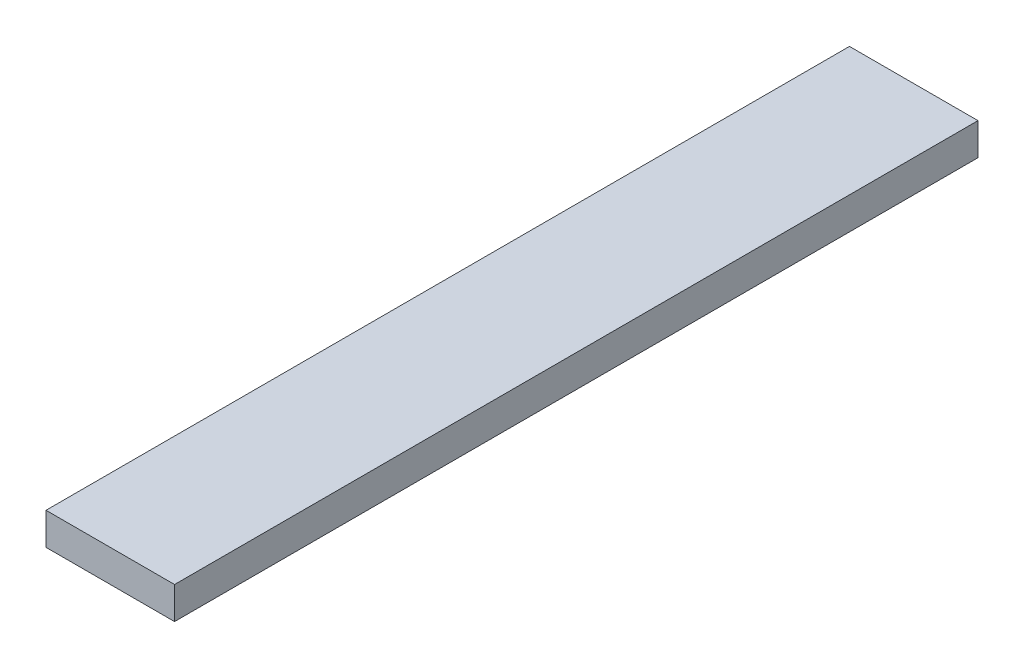
SolidWorks part; units mm, degrees
material "Beech"
ref_plane "Front Plane" through (0, 0, 0) normal (0, 0, 1) x (1, 0, 0)
ref_plane "Top Plane" through (0, 0, 0) normal (0, 1, 0) x (1, 0, 0)
ref_plane "Right Plane" through (0, 0, 0) normal (1, 0, 0) x (0, 0, -1)
sketch "Sketch1" plane through (0, 0, 0) normal (0, 1, 0) x (1, 0, 0)
  line L1 (0, 0) -> (304.8, 0)
  line L2 (0, 0) -> (0, 304.8)
  line L3 (0, 304.8) -> (304.8, 304.8)
  line L4 (304.8, 0) -> (304.8, 304.8)
  dimension "D1" = 304.8
  dimension "D2" = 304.8
extrude "Boss-Extrude1" add sketch "Sketch1" along normal blind 6.35
sketch "Sketch2" plane through (0, 6.35, 0) normal (0, 1, 0) x (1, 0, 0)
  line L1 (304.8, 304.8) -> (0, 304.8) construction
  line L2 (25.4, 304.8) -> (25.4, 146.05)
  line L3 (25.4, 146.05) -> (0, 146.05)
  line L4 (0, 304.8) -> (0, 0) construction
  line L6 (0, 146.05) -> (0, 0)
  line L7 (0, 0) -> (304.8, 0)
  line L8 (304.8, 0) -> (304.8, 304.8)
  line L9 (304.8, 304.8) -> (25.4, 304.8)
  dimension "D1" = 25.4
  dimension "D2" = 158.75
extrude "Cut-Extrude2" cut sketch "Sketch2" against normal blind 6.35 contours L3 L6 L7 L8 L9 L2
